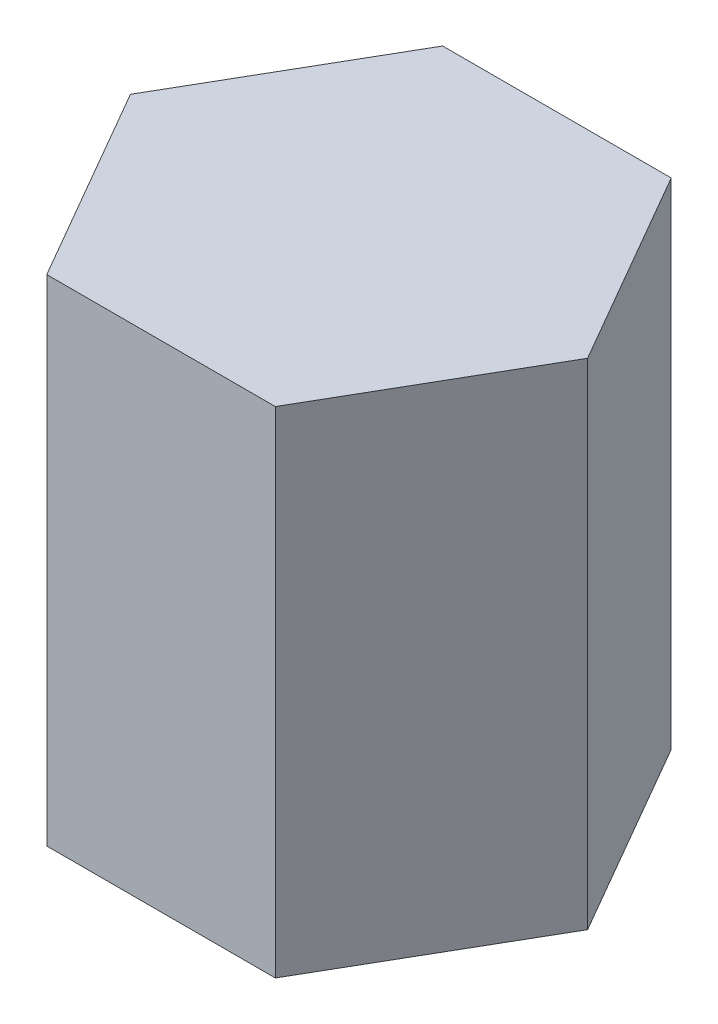
SolidWorks part; units mm, degrees
ref_plane "Front Plane" through (0, 0, 0) normal (0, 0, 1) x (1, 0, 0)
ref_plane "Top Plane" through (0, 0, 0) normal (0, 1, 0) x (1, 0, 0)
ref_plane "Right Plane" through (0, 0, 0) normal (1, 0, 0) x (0, 0, -1)
sketch "Sketch1" plane through (0, 0, 0) normal (0, 1, 0) x (1, 0, 0)
  line L1 (23.094, 0) -> (11.547, 20)
  line L2 (11.547, 20) -> (-11.547, 20)
  line L3 (-11.547, 20) -> (-23.094, 0)
  line L4 (-23.094, 0) -> (-11.547, -20)
  line L5 (-11.547, -20) -> (11.547, -20)
  line L6 (11.547, -20) -> (23.094, 0)
  circle A0 centre (0, 0) radius 9.67
  circle A1 centre (0, 0) radius 20 construction
  dimension "D2" = 40
extrude "Boss-Extrude1" add sketch "Sketch1" along normal blind 50
sketch "Sketch2" plane through (0, 50, 0) normal (0, 1, 0) x (1, 0, 0)
  circle A0 centre (0, 0) radius 9.67 construction
  circle A1 centre (0, 0) radius 9.67
extrude "Boss-Extrude2" add sketch "Sketch2" against normal blind 3
